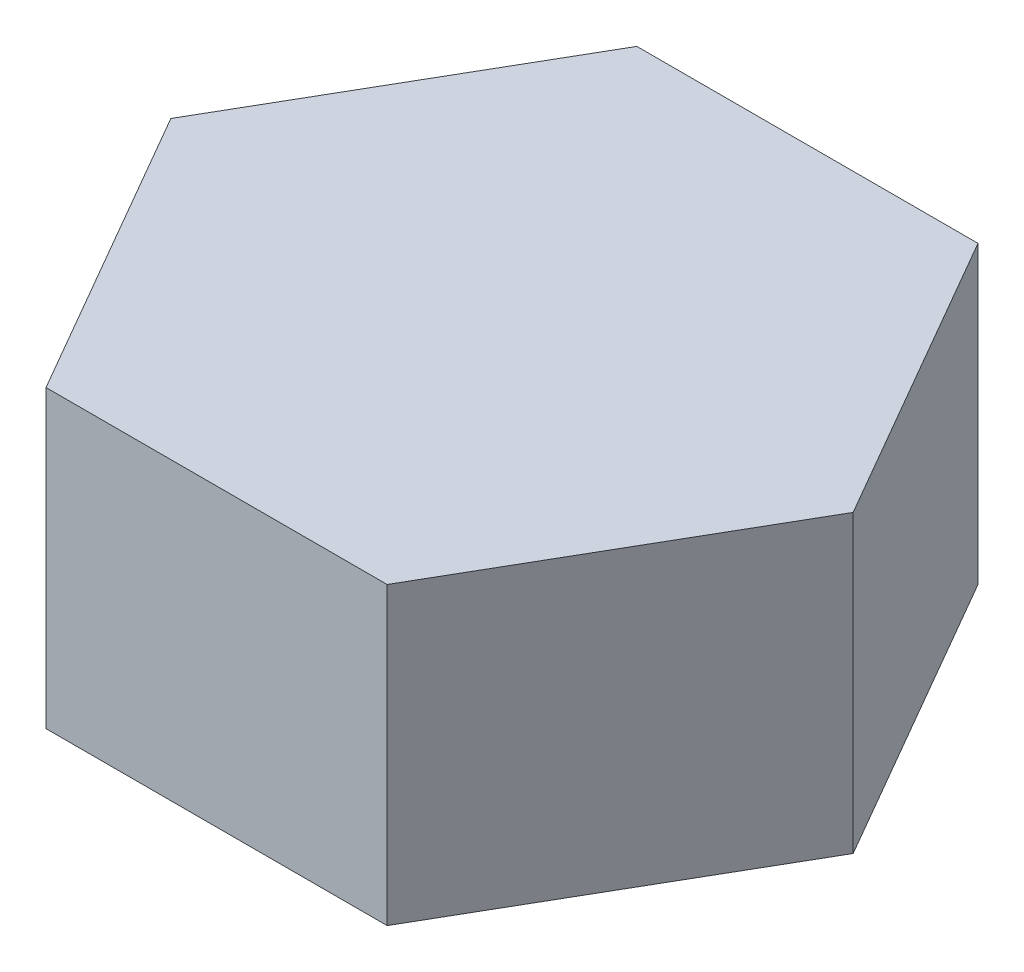
SolidWorks part; units mm, degrees
ref_plane "Front Plane" through (0, 0, 0) normal (0, 0, 1) x (1, 0, 0)
ref_plane "Top Plane" through (0, 0, 0) normal (0, 1, 0) x (1, 0, 0)
ref_plane "Right Plane" through (0, 0, 0) normal (1, 0, 0) x (0, 0, -1)
sketch "Sketch2" plane through (0, 0, 0) normal (0, 1, 0) x (1, 0, 0)
  line L1 (5.7735, 0) -> (2.8868, 5)
  line L2 (2.8868, 5) -> (-2.8868, 5)
  line L3 (-2.8868, 5) -> (-5.7735, 0)
  line L4 (-5.7735, 0) -> (-2.8868, -5)
  line L5 (-2.8868, -5) -> (2.8868, -5)
  line L6 (2.8868, -5) -> (5.7735, 0)
  circle A0 centre (0, 0) radius 5 construction
  circle A1 centre (0, 0) radius 3
  point P10 (0, 5)
  dimension "D1" = 6
  dimension "D2" = 10
extrude "Boss-Extrude2" add sketch "Sketch2" along normal mid plane 5 contours A1 | L5 L6 L1 L2 L3 L4 A1
